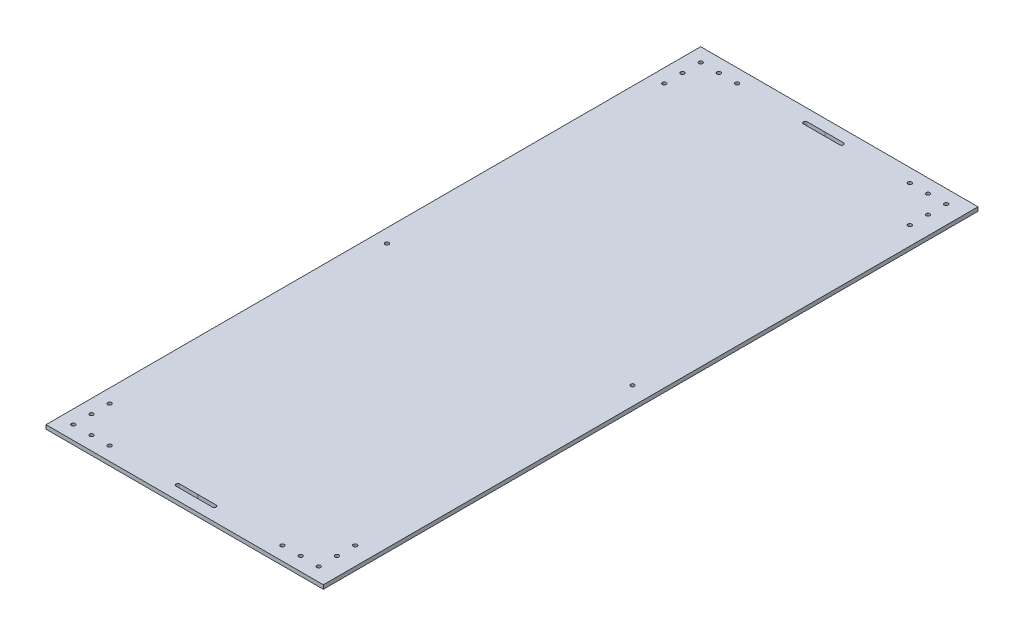
SolidWorks part; units mm, degrees
ref_plane "Front Plane" through (0, 0, 0) normal (0, 0, 1) x (1, 0, 0)
ref_plane "Top Plane" through (0, 0, 0) normal (0, 1, 0) x (1, 0, 0)
ref_plane "Right Plane" through (0, 0, 0) normal (1, 0, 0) x (0, 0, -1)
sketch "Sketch1" plane through (0, 0, 0) normal (0, 1, 0) x (1, 0, 0)
  line L1 (0, 0) -> (609.6, 0)
  line L2 (0, 0) -> (0, 1219.2)
  line L3 (0, 1219.2) -> (609.6, 1219.2)
  line L4 (609.6, 0) -> (609.6, 1219.2)
  dimension "D1" = 609.6
  dimension "D2" = 1219.2
extrude "Boss-Extrude1" add sketch "Sketch1" along normal blind 5.5
sketch "Sketch3" plane through (0, 5.5, 0) normal (0, 1, 0) x (1, 0, 0)
  line L0 (387.35, 0) -> (387.35, 914.4)
  line L5 (0, 0) -> (609.6, 0) construction
  line L6 (0, 1219.2) -> (0, 0) construction
  line L7 (387.35, 914.4) -> (0, 914.4)
  line L12 (0, 1219.2) -> (0, 0)
  line L13 (0, 0) -> (609.6, 0)
  line L14 (609.6, 0) -> (609.6, 1219.2)
  line L15 (609.6, 1219.2) -> (0, 1219.2)
  line L16 (0, 1219.2) -> (0, 914.4)
  line L17 (387.35, 0) -> (609.6, 0)
  line L18 (609.6, 0) -> (609.6, 1219.2)
  line L19 (609.6, 1219.2) -> (0, 1219.2)
  dimension "D1" = 387.35
  dimension "D2" = 914.4
  dimension "D3" = 0
extrude "Boss-Extrude2" add sketch "Sketch3" along normal blind 6.35
sketch "Sketch4" plane through (0, 5.5, 0) normal (0, 1, 0) x (1, 0, 0)
  line L0 (19.05, 895.35) -> (19.05, 19.05) construction
  line L1 (0, 914.4) -> (387.35, 914.4) construction
  line L2 (0, 0) -> (387.35, 0) construction
  line L3 (0, 914.4) -> (0, 0) construction
  line L4 (361.95, 895.35) -> (361.95, 19.05) construction
  line L6 (387.35, 914.4) -> (387.35, 0) construction
  line L7 (19.05, 19.05) -> (361.95, 19.05) construction
  line L8 (19.05, 895.35) -> (361.95, 895.35) construction
  line L9 (190.5, 19.05) -> (190.5, 895.35) construction
  line L10 (19.05, 457.2) -> (361.95, 457.2) construction
  point P0 (44.45, 19.05)
  point P1 (19.05, 19.05)
  point P8 (69.85, 19.05)
  point P9 (19.05, 44.45)
  point P10 (19.05, 69.85)
  point P21 (361.95, 69.85)
  point P22 (361.95, 44.45)
  point P23 (361.95, 19.05)
  point P24 (336.55, 19.05)
  point P25 (311.15, 19.05)
  point P26 (361.95, 844.55)
  point P27 (361.95, 869.95)
  point P28 (336.55, 895.35)
  point P29 (311.15, 895.35)
  point P30 (19.05, 844.55)
  point P31 (19.05, 869.95)
  point P32 (19.05, 895.35)
  point P33 (44.45, 895.35)
  point P34 (69.85, 895.35)
  dimension "D1" = 19.05
  dimension "D2" = 25.4
  dimension "D3" = 19.05
  dimension "D4" = 19.05
  dimension "D5" = 25.4
  dimension "D6" = 25.4
  dimension "D7" = 25.4
  dimension "D8" = 25.4
hole_wizard "Ø5.3 (5.3) Diameter Hole1" positions "Sketch5" profile "Sketch6" hole size "Ø5.3" standard "ANSI Metric" end condition through all
sketch "Sketch5" plane through (0, 5.5, 0) normal (0, 1, 0) x (1, 0, 0)
  point P0 (19.05, 895.35)
  point P3 (44.45, 895.35)
  point P6 (69.85, 895.35)
  point P9 (19.05, 869.95)
  point P12 (19.05, 844.55)
  point P15 (19.05, 457.2)
  point P18 (19.05, 69.85)
  point P21 (19.05, 44.45)
  point P24 (19.05, 19.05)
  point P27 (44.45, 19.05)
  point P30 (69.85, 19.05)
  point P33 (190.5, 19.05)
  point P36 (311.15, 19.05)
  point P39 (336.55, 19.05)
  point P42 (361.95, 19.05)
  point P45 (361.95, 44.45)
  point P48 (361.95, 69.85)
  point P51 (361.95, 457.2)
  point P54 (361.95, 844.55)
  point P57 (361.95, 869.95)
  point P60 (361.95, 895.35)
  point P63 (336.55, 895.35)
  point P66 (311.15, 895.35)
  point P69 (190.5, 895.35)
sketch "Sketch6" plane through (19.05, 5.5, -895.35) normal (1, 0, 0) x (0, 0, 1)
  line L0 (0, 0) -> (0, 5.5)
  line L1 (0, 5.5) -> (2.65, 5.5)
  line L2 (2.65, 5.5) -> (2.65, 0)
  line L5 (2.65, 0) -> (0, 0)
  line L11 (0, -6.35) -> (0, 107.95) construction
  dimension "Thru Hole Dia." = 5.3
  dimension "Thru Hole Depth" = 5.5
sketch "Sketch7" plane through (0, 11.85, 0) normal (0, 1, 0) x (1, 0, 0)
  line L0 (0, 1219.2) -> (0, 914.4)
  line L1 (0, 914.4) -> (387.35, 914.4)
  line L2 (387.35, 914.4) -> (387.35, 0)
  line L3 (387.35, 0) -> (609.6, 0)
  line L4 (609.6, 0) -> (609.6, 1219.2)
  line L5 (0, 1219.2) -> (609.6, 1219.2)
extrude "Cut-Extrude1" cut sketch "Sketch7" against normal up to next
sketch "Sketch8" plane through (0, 5.5, 0) normal (0, 1, 0) x (1, 0, 0)
  line L0 (190.5, 19.05) -> (215.9, 19.05) construction
  line L1 (190.5, 21.65) -> (215.9, 21.65)
  line L2 (190.5, 16.45) -> (215.9, 16.45)
  line L3 (0, 19.05) -> (387.35, 19.05) construction
  line L4 (0, 914.4) -> (0, 0) construction
  line L5 (387.35, 914.4) -> (387.35, 0) construction
  line L6 (165.1, 19.05) -> (190.5, 19.05) construction
  line L7 (165.1, 21.65) -> (190.5, 21.65)
  line L8 (165.1, 16.45) -> (190.5, 16.45)
  line L9 (190.5, 895.35) -> (190.5, 914.4) construction
  line L10 (0, 914.4) -> (387.35, 914.4) construction
  line L11 (0, 0) -> (387.35, 0) construction
  line L12 (19.05, 457.2) -> (361.95, 457.2) construction
  line L13 (165.1, 895.35) -> (190.5, 895.35) construction
  line L14 (165.1, 892.75) -> (190.5, 892.75)
  line L15 (165.1, 897.95) -> (190.5, 897.95)
  line L16 (190.5, 895.35) -> (215.9, 895.35) construction
  line L17 (190.5, 892.75) -> (215.9, 892.75)
  line L18 (190.5, 897.95) -> (215.9, 897.95)
  arc A0 (190.5, 21.65) -> (190.5, 16.45) centre (190.5, 19.05) ccw
  arc A1 (215.9, 16.45) -> (215.9, 21.65) centre (215.9, 19.05) ccw
  arc A2 (165.1, 892.75) -> (165.1, 897.95) centre (165.1, 895.35) cw
  arc A5 (165.1, 21.65) -> (165.1, 16.45) centre (165.1, 19.05) ccw
  arc A6 (190.5, 16.45) -> (190.5, 21.65) centre (190.5, 19.05) ccw
  arc A7 (190.5, 897.95) -> (190.5, 892.75) centre (190.5, 895.35) cw
  arc A8 (190.5, 892.75) -> (190.5, 897.95) centre (190.5, 895.35) cw
  arc A9 (215.9, 897.95) -> (215.9, 892.75) centre (215.9, 895.35) cw
  point P2 (203.2, 19.05)
  point P19 (177.8, 19.05)
  point P34 (177.8, 895.35)
  point P41 (203.2, 895.35)
  circle M24 centre (190.5, 19.05) radius 2.65
  circle M36 centre (190.5, 895.35) radius 2.65
  dimension "D2" = 25.4
  dimension "D1" = 5.2
  dimension "D4" = 19.05
extrude "Cut-Extrude2" cut sketch "Sketch8" against normal through all contours L7 A5 L8 M24 | A0 A6 | L2 A1 L1 M24 | A2 L14 L15 M36 | A8 A7 | A9 L18 L17 M36
